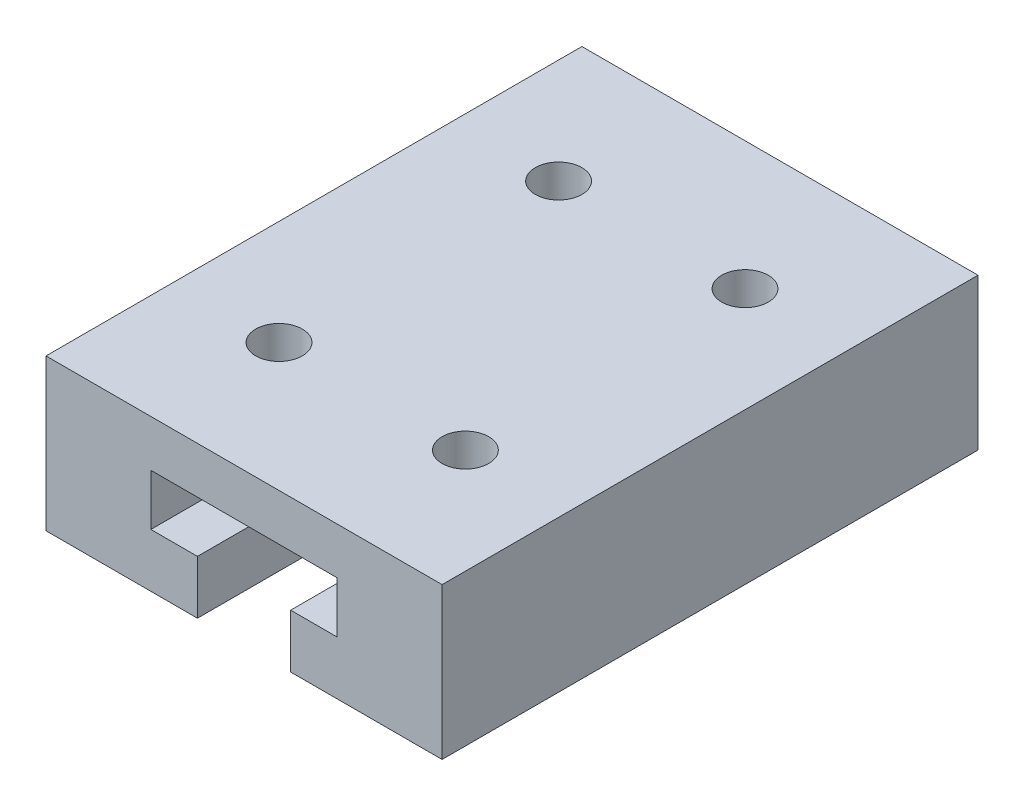
SolidWorks part; units mm, degrees
ref_plane "Płaszczyzna przednia" through (0, 0, 0) normal (0, 0, 1) x (1, 0, 0)
ref_plane "Płaszczyzna górna" through (0, 0, 0) normal (0, 1, 0) x (1, 0, 0)
ref_plane "Płaszczyzna prawa" through (0, 0, 0) normal (1, 0, 0) x (0, 0, -1)
sketch "Szkic1" plane through (0, 0, 0) normal (0, 0, 1) x (1, 0, 0)
  line L0 (0, 0) -> (0, 2)
  line L1 (0, 2) -> (-8.5, 2)
  line L2 (-8.5, 2) -> (-8.5, -4.5)
  line L3 (-8.5, -4.5) -> (-2, -4.5)
  line L4 (-2, -4.5) -> (-2, -2.2)
  line L5 (-2, -2.2) -> (-4, -2.2)
  line L6 (-4, -2.2) -> (-4, 0)
  line L7 (-4, 0) -> (0, 0)
  dimension "D1" = 8.5
  dimension "D2" = 6.5
  dimension "D3" = 2
  dimension "D4" = 2
  dimension "D5" = 2.2
  dimension "D6" = 4
extrude "Dodanie-wyciągnięcie1" add sketch "Szkic1" along normal blind 23
mirror "Lustro1" about plane through (0, 0, 23) normal (-1, 0, 0) of "Dodanie-wyciągnięcie1"
sketch "Szkic2" plane through (0, 2, 0) normal (0, 1, 0) x (1, 0, 0)
  line L1 (-8.5, -23) -> (-8.5, 0) construction
  circle A0 centre (-4, -5.5) radius 1
  circle A1 centre (4, -5.5) radius 1
  circle A2 centre (4, -17.5) radius 1
  circle A3 centre (-4, -17.5) radius 1
  point P4 (-8.5, -11.5)
  dimension "D1" = 2
  dimension "D3" = 4
  dimension "D4" = 6
  dimension "D2" = 2
extrude "Wytnij-wyciągnięcie1" cut sketch "Szkic2" against normal blind 1.5
